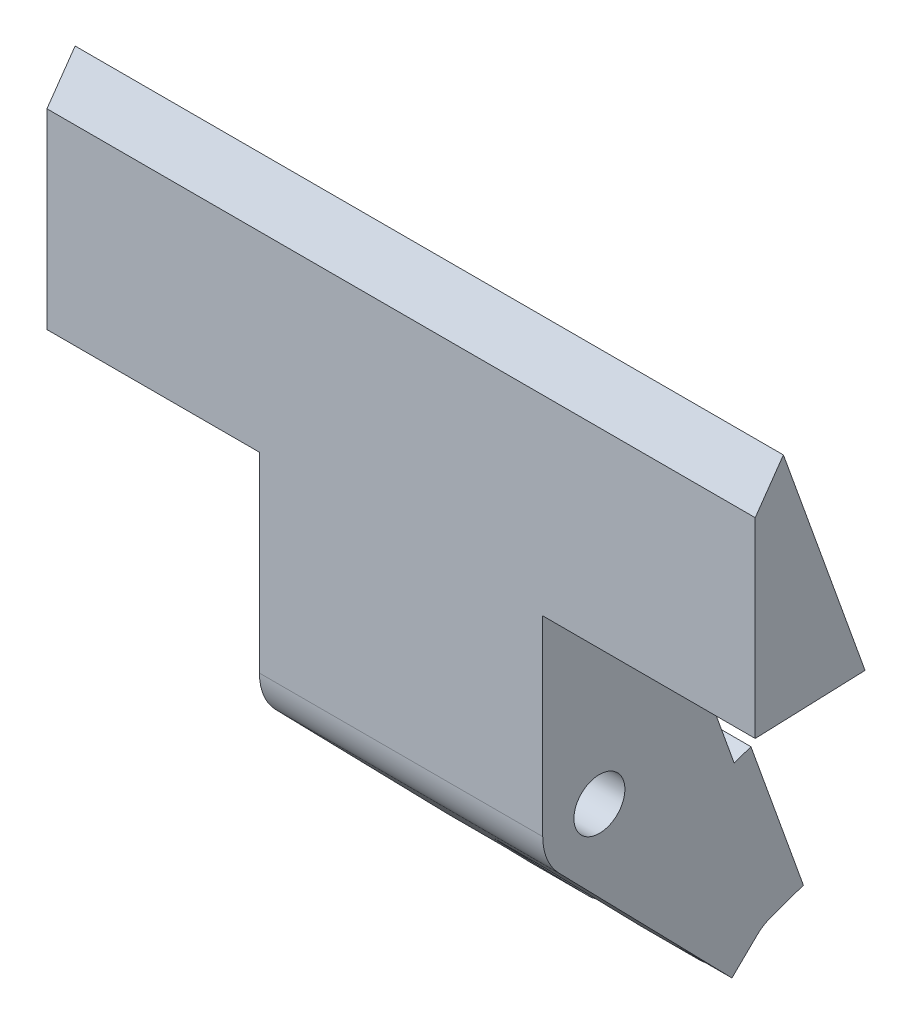
SolidWorks part; units mm, degrees
material "ABS PC"
ref_plane "Front Plane" through (0, 0, 0) normal (0, 0, 1) x (1, 0, 0)
ref_plane "Top Plane" through (0, 0, 0) normal (0, 1, 0) x (1, 0, 0)
ref_plane "Right Plane" through (0, 0, 0) normal (1, 0, 0) x (0, 0, -1)
ref_plane "Plane4" through (-34.925, 0, 0) normal (1, 0, 0) x (0, 0, -1)
sketch "Sketch1" plane through (-34.925, 0, 0) normal (1, 0, 0) x (0, 0, -1)
  line L0 (38.7218, -36.8786) -> (-2.8756, 78.9832)
  line L1 (0, 0) -> (32.7453, -39.0244) construction
  line L2 (-2.8756, 78.9832) -> (-10.16, 68.58)
  line L3 (-10.16, 68.58) -> (-10.16, 0)
  line L4 (-7.2728, -7.0945) -> (28.1998, -43.4584)
  line L5 (0, 0) -> (51.2975, 0) construction
  arc A0 (-10.16, 0) -> (-7.2728, -7.0945) centre (0, 0) ccw
  arc A1 (28.1998, -43.4584) -> (38.7218, -36.8786) centre (32.7453, -39.0244) ccw
  dimension "D1" = 6.35
  dimension "D2" = 10.16
  dimension "D3" = 50.8
  dimension "D4" = 50
  dimension "D5" = 145
  dimension "D6" = 12.7
  dimension "D7" = 68.58
extrude "Boss-Extrude1" add sketch "Sketch1" against normal blind 50.8
scale "Scale1" scale about centroid uniform scaling yes scale factor 0.5
sketch "Sketch2" plane through (-47.625, 0, 0) normal (1, 0, 0) x (0, 0, -1)
  circle A0 centre (20.7214, -14.3975) radius 1.3462
  dimension "D1" = 2.6924
extrude "Cut-Extrude1" cut sketch "Sketch2" against normal through all
sketch "Sketch3" plane through (-47.625, 0, 0) normal (1, 0, 0) x (0, 0, -1)
  circle A0 centre (4.3487, 5.1147) radius 2.286
  dimension "D1" = 4.572
extrude "Cut-Extrude2" cut sketch "Sketch3" against normal through all
ref_plane "Plane5" through (-60.325, 0, 0) normal (1, 0, 0) x (0, 0, -1)
sketch "Sketch4" plane through (-60.325, 0, 0) normal (1, 0, 0) x (0, 0, -1)
  line L0 (9.5805, -7.5235) -> (18.4486, -16.6145)
  line L1 (0.7123, 1.5675) -> (18.4486, -16.6145) construction
  line L2 (23.7096, -13.3246) -> (18.5023, 1.1796)
  line L3 (23.7096, -13.3246) -> (2.9109, 44.6063) construction
  line L4 (18.5023, 1.1796) -> (9.5805, -7.5235)
  arc A0 (18.4486, -16.6145) -> (23.7096, -13.3246) centre (20.7214, -14.3975) ccw
extrude "Cut-Extrude3" cut sketch "Sketch4" against normal mid plane 4.572
sketch "Sketch5" plane through (-47.625, 0, 0) normal (1, 0, 0) x (0, 0, -1)
  line L0 (1.7959, 43.0139) -> (16.4368, 2.2345)
  line L1 (2.9109, 44.6063) -> (-0.7313, 39.4047) construction
  line L2 (16.4368, 2.2345) -> (17.9309, 2.7709)
  line L3 (23.7096, -13.3246) -> (2.9109, 44.6063) construction
  line L4 (17.9309, 2.7709) -> (2.9109, 44.6063)
  line L5 (2.9109, 44.6063) -> (1.7959, 43.0139)
  dimension "D1" = 1.5875
  dimension "D2" = 44.45
extrude "Cut-Extrude4" cut sketch "Sketch5" against normal through all
sketch "Sketch6" plane through (-60.325, 0, 0) normal (1, 0, 0) x (0, 0, -1)
  line L0 (-0.7313, 22.2597) -> (-0.7313, 39.4047)
  line L1 (-0.7313, 39.4047) -> (-0.7313, 5.1147) construction
  line L2 (-0.7313, 39.4047) -> (1.7959, 43.0139)
  line L3 (1.7959, 43.0139) -> (9.1164, 22.6242)
  line L4 (1.7959, 43.0139) -> (16.4368, 2.2345) construction
  line L5 (9.1164, 22.6242) -> (-0.7313, 22.2597)
extrude "Boss-Extrude2" add sketch "Sketch6" along normal mid plane 63.5
sketch "Sketch7" plane through (-47.625, 0, 0) normal (1, 0, 0) x (0, 0, -1)
  line L0 (19.6485, -11.4092) -> (22.6368, -10.3364)
  line L1 (23.7096, -13.3246) -> (17.9309, 2.7709) construction
  line L2 (16.2316, -14.3418) -> (18.5043, -12.1247)
  line L3 (0.7123, 1.5675) -> (18.4486, -16.6145) construction
  line L4 (22.6368, -10.3364) -> (23.7096, -13.3246)
  line L5 (16.2316, -14.3418) -> (18.4486, -16.6145)
  circle A0 centre (20.7214, -14.3975) radius 3.175
  arc A1 (18.4486, -16.6145) -> (23.7096, -13.3246) centre (20.7214, -14.3975) ccw construction
  circle M3 centre (20.7214, -14.3975) radius 1.3462
  line M8 (0.7123, 1.5675) -> (18.4486, -16.6145)
  arc M9 (18.4486, -16.6145) -> (23.7096, -13.3246) centre (20.7214, -14.3975) ccw
  line M10 (23.7096, -13.3246) -> (17.9309, 2.7709)
extrude "Cut-Extrude5" cut sketch "Sketch7" against normal blind 5.08 contours A0 M9 M3 | A0 L2 M8 | A0 L0 M10
mirror "Mirror1" about plane through (-60.325, 0, 0) normal (1, 0, 0) of "Cut-Extrude5"
